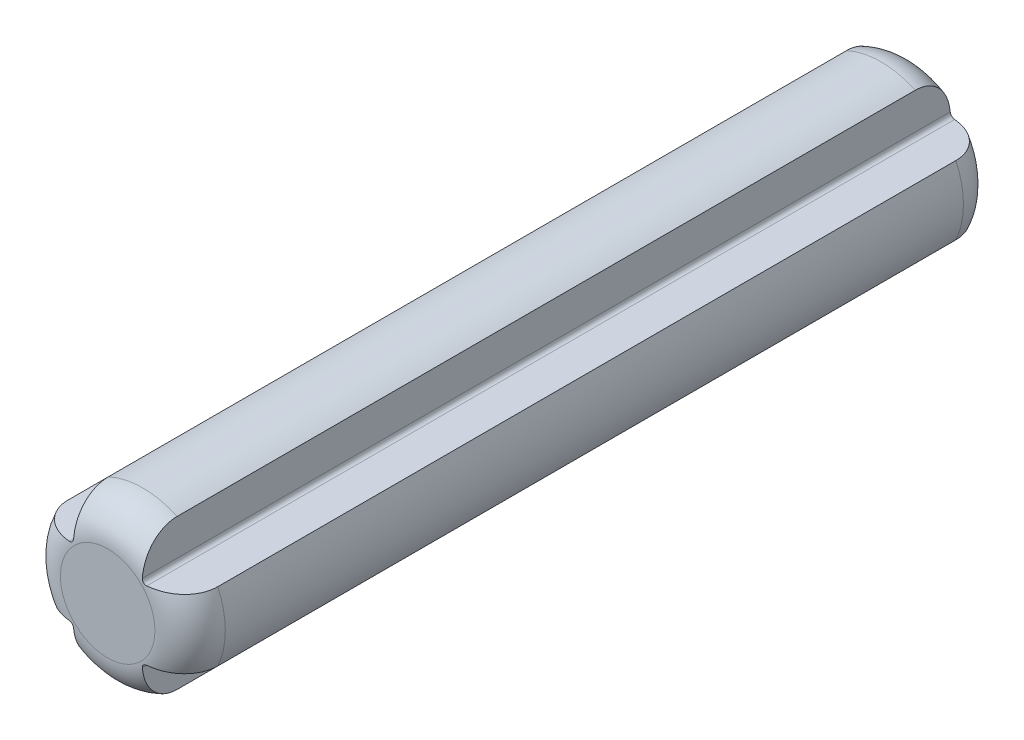
SolidWorks part; units mm, degrees
ref_plane "Front Plane" through (0, 0, 0) normal (0, 0, 1) x (1, 0, 0)
ref_plane "Top Plane" through (0, 0, 0) normal (0, 1, 0) x (1, 0, 0)
ref_plane "Right Plane" through (0, 0, 0) normal (1, 0, 0) x (0, 0, -1)
sketch "Sketch1" plane through (0, 0, 0) normal (0, 0, 1) x (1, 0, 0)
  circle A0 centre (0, 0) radius 2.3813
  dimension "D1" = 4.7625
extrude "Extrude1" add sketch "Sketch1" along normal mid plane 23.3531
fillet "Fillet1" radius 1.016 2 edges at (2.3813, 0, -11.6766) (2.3813, 0, 11.6766)
sketch "Sketch3" plane through (0, 0, 0) normal (0, 0, 1) x (1, 0, 0)
  line L0 (-0.9922, 2.1647) -> (-0.9922, 1.1192)
  line L1 (-1.1192, 0.9922) -> (-2.1647, 0.9922)
  line L2 (-2.1647, -0.9922) -> (-1.1192, -0.9922)
  line L3 (-0.9922, -1.1192) -> (-0.9922, -2.1647)
  line L4 (0.9922, 2.1647) -> (0.9922, 1.1192)
  line L5 (1.1192, 0.9922) -> (2.1647, 0.9922)
  line L6 (0.9922, -1.1192) -> (0.9922, -2.1647)
  line L7 (1.1192, -0.9922) -> (2.1647, -0.9922)
  line L8 (0, 2.3813) -> (0, -2.3813) construction
  line L9 (-2.3813, 0) -> (2.3813, 0) construction
  circle A0 centre (0, 0) radius 2.3813 construction
  arc A1 (-0.9922, 2.1647) -> (-2.1647, 0.9922) centre (0, 0) ccw
  arc A2 (-0.9922, 1.1192) -> (-1.1192, 0.9922) centre (-1.1192, 1.1192) cw
  arc A3 (0.9922, 1.1192) -> (1.1192, 0.9922) centre (1.1192, 1.1192) ccw
  arc A4 (-1.1192, -0.9922) -> (-0.9922, -1.1192) centre (-1.1192, -1.1192) cw
  arc A5 (0.9922, -1.1192) -> (1.1192, -0.9922) centre (1.1192, -1.1192) cw
  arc A6 (2.1647, 0.9922) -> (0.9922, 2.1647) centre (0, 0) ccw
  arc A7 (0.9922, -2.1647) -> (2.1647, -0.9922) centre (0, 0) ccw
  arc A8 (-2.1647, -0.9922) -> (-0.9922, -2.1647) centre (0, 0) ccw
  point P23 (0.9922, 0.9922)
  dimension "D3" = 0.127
  dimension "D1" = 1.9844
  dimension "D2" = 1.9844
extrude "Extrude2" cut sketch "Sketch3" against normal through all and the other way through all
